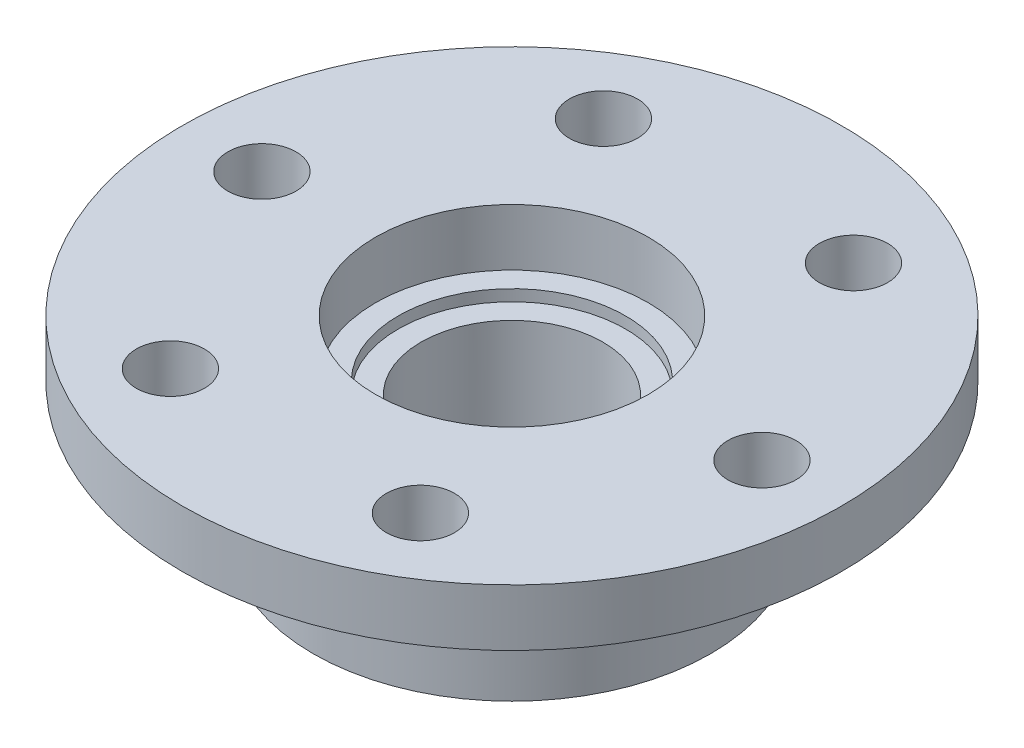
SolidWorks part; units mm, degrees
ref_plane "Front Plane" through (0, 0, 0) normal (0, 0, 1) x (1, 0, 0)
ref_plane "Top Plane" through (0, 0, 0) normal (0, 1, 0) x (1, 0, 0)
ref_plane "Right Plane" through (0, 0, 0) normal (1, 0, 0) x (0, 0, -1)
sketch "Sketch1" plane through (0, 0, 0) normal (0, 1, 0) x (1, 0, 0)
  circle A0 centre (0, 0) radius 17.5
  dimension "D1" = 35
extrude "Boss-Extrude1" add sketch "Sketch1" along normal blind 12
sketch "Sketch2" plane through (0, 12, 0) normal (0, 1, 0) x (1, 0, 0)
  circle A0 centre (0, 0) radius 29
  dimension "D1" = 58
extrude "Boss-Extrude2" add sketch "Sketch2" along normal blind 5
sketch "Sketch3" plane through (0, 17, 0) normal (0, 1, 0) x (1, 0, 0)
  circle A0 centre (0, 0) radius 12
  dimension "D1" = 24
extrude "Cut-Extrude1" cut sketch "Sketch3" against normal blind 5
sketch "Sketch4" plane through (0, 12, 0) normal (0, 1, 0) x (1, 0, 0)
  circle A3 centre (0, 0) radius 10
  circle A4 centre (0, 0) radius 10
  dimension "D1" = 2
extrude "Cut-Extrude2" cut sketch "Sketch4" against normal blind 1
sketch "Sketch5" plane through (0, 12, 0) normal (0, -1, 0) x (1, 0, 0)
  line L0 (0, 0) -> (22, 0) construction
  circle A0 centre (22, 0) radius 3
  circle A1 centre (11, -19.0526) radius 3
  circle A2 centre (-11, -19.0526) radius 3
  circle A3 centre (-22, 0) radius 3
  circle A4 centre (-11, 19.0526) radius 3
  circle A5 centre (11, 19.0526) radius 3
  point P16 (0, 0)
  dimension "D2" = 6
  dimension "D1" = 22
  dimension "D3" = 6
extrude "Cut-Extrude3" cut sketch "Sketch5" against normal up to next
sketch "Sketch6" plane through (0, 12, 0) normal (0, -1, 0) x (1, 0, 0)
  circle A0 centre (0, 0) radius 17.5 construction
  circle A1 centre (0, 0) radius 17.5
  circle A2 centre (0, 0) radius 18.8
  dimension "D1" = 1.3
extrude "Boss-Extrude3" add sketch "Sketch6" along normal blind 0.9
sketch "Sketch7" plane through (0, 0, 0) normal (0, -1, 0) x (1, 0, 0)
  circle A1 centre (0, 0) radius 8
  dimension "D1" = 16
extrude "Cut-Extrude4" cut sketch "Sketch7" against normal up to next
sketch "Sketch9" plane through (0, 0, 0) normal (0, -1, 0) x (1, 0, 0)
  line L0 (0, 0) -> (0, 8) construction
  line L1 (0, 8) -> (0, 17.5) construction
  circle A0 centre (0, 0) radius 8 construction
  circle A1 centre (0, 0) radius 17.5 construction
  circle A2 centre (0, 12.75) radius 2.7
  circle A3 centre (11.0418, 6.375) radius 2.7
  circle A4 centre (11.0418, -6.375) radius 2.7
  circle A5 centre (0, -12.75) radius 2.7
  circle A6 centre (-11.0418, -6.375) radius 2.7
  circle A7 centre (-11.0418, 6.375) radius 2.7
  point P25 (0, 0)
  dimension "D1" = 5.4
  dimension "D2" = 6
extrude "Cut-Extrude5" cut sketch "Sketch9" against normal blind 10
